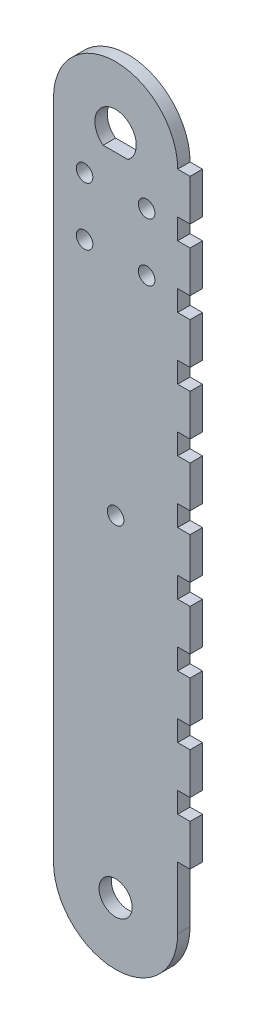
SolidWorks part; units mm, degrees
material "Thornel Mat VMA"
ref_plane "前视基准面" through (0, 0, 0) normal (0, 0, 1) x (1, 0, 0)
ref_plane "上视基准面" through (0, 0, 0) normal (0, 1, 0) x (1, 0, 0)
ref_plane "右视基准面" through (0, 0, 0) normal (1, 0, 0) x (0, 0, -1)
sketch "草图1" plane through (0, 0, 0) normal (0, 0, 1) x (1, 0, 0)
  line L0 (-15, 0) -> (-15, -160)
  line L1 (15, 0) -> (15, -160)
  line L3 (0, -55) -> (0, 55) construction
  line L4 (0, -4) -> (3, -4)
  line L5 (0, -4) -> (-3, -4)
  arc A0 (15, 0) -> (-15, 0) centre (0, 0) ccw
  arc A1 (-15, -160) -> (15, -160) centre (0, -160) ccw
  circle A2 centre (0, -160) radius 4
  arc A3 (3, -4) -> (-3, -4) centre (0, 0) ccw
  circle A4 centre (-7.5, -12) radius 2
  circle A5 centre (-7.5, -26) radius 2
  circle A6 centre (7.5, -26) radius 2
  circle A7 centre (7.5, -12) radius 2
  dimension "D1" = 7.5
  dimension "D2" = 14
  dimension "D3" = 12
  dimension "D4" = 160
  dimension "D5" = 160
extrude "凸台-拉伸1" add sketch "草图1" along normal blind 3
sketch "草图3" plane through (0, 0, 3) normal (0, 0, 1) x (1, 0, 0)
  line L0 (15, -160) -> (15, 0) construction
  line L1 (15, 0) -> (18, 0)
  line L2 (15, 0) -> (15, -10)
  line L3 (15, -10) -> (18, -10)
  line L4 (18, 0) -> (18, -10)
  line L5 (15, -15) -> (15, -25)
  line L6 (15, -15) -> (18, -15)
  line L7 (18, -15) -> (18, -25)
  line L8 (15, -25) -> (18, -25)
  line L9 (15, -30) -> (15, -40)
  line L10 (15, -30) -> (18, -30)
  line L11 (18, -30) -> (18, -40)
  line L12 (15, -40) -> (18, -40)
  line L13 (15, -45) -> (15, -55)
  line L14 (15, -45) -> (18, -45)
  line L15 (18, -45) -> (18, -55)
  line L16 (15, -55) -> (18, -55)
  line L17 (15, -60) -> (15, -70)
  line L18 (15, -60) -> (18, -60)
  line L19 (18, -60) -> (18, -70)
  line L20 (15, -70) -> (18, -70)
  line L21 (15, -75) -> (15, -85)
  line L22 (15, -75) -> (18, -75)
  line L23 (18, -75) -> (18, -85)
  line L24 (15, -85) -> (18, -85)
  line L25 (15, -90) -> (15, -100)
  line L26 (15, -90) -> (18, -90)
  line L27 (18, -90) -> (18, -100)
  line L28 (15, -100) -> (18, -100)
  line L29 (15, -105) -> (15, -115)
  line L30 (15, -105) -> (18, -105)
  line L31 (18, -105) -> (18, -115)
  line L32 (15, -115) -> (18, -115)
  line L33 (15, -120) -> (15, -130)
  line L34 (15, -120) -> (18, -120)
  line L35 (18, -120) -> (18, -130)
  line L36 (15, -130) -> (18, -130)
  line L37 (15, -135) -> (15, -145)
  line L38 (15, -135) -> (18, -135)
  line L39 (18, -135) -> (18, -145)
  line L40 (15, -145) -> (18, -145)
  arc A0 (15, 0) -> (-15, 0) centre (0, 0) ccw construction
  dimension "D1" = 3
  dimension "D2" = 10
  dimension "D3" = 10
extrude "凸台-拉伸4" add sketch "草图3" against normal blind 3
sketch "草图4" plane through (0, 0, 3) normal (0, 0, 1) x (1, 0, 0)
  line L0 (0, -1.65) -> (0, 1.65) construction
  circle A0 centre (0, -80) radius 2
extrude "切除-拉伸1" cut sketch "草图4" against normal blind 3
